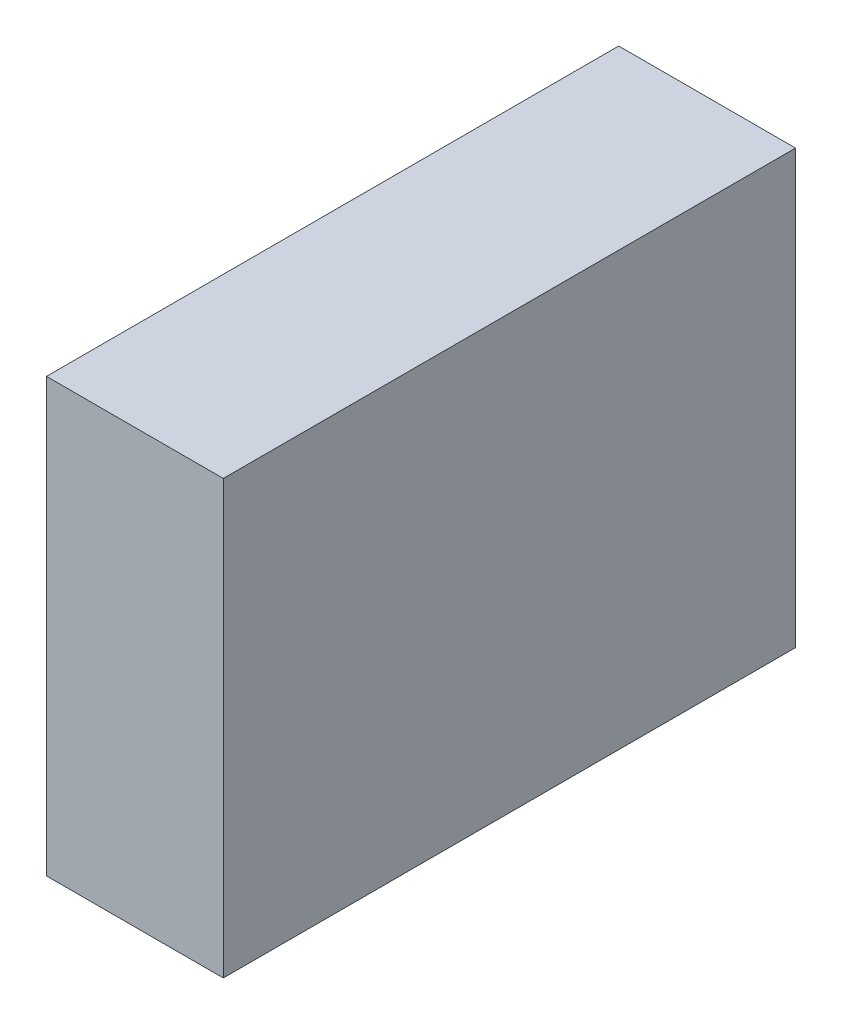
SolidWorks part; units mm, degrees
ref_plane "Front" through (0, 0, 0) normal (0, 0, 1) x (1, 0, 0)
ref_plane "Top" through (0, 0, 0) normal (0, 1, 0) x (1, 0, 0)
ref_plane "Right" through (0, 0, 0) normal (1, 0, 0) x (0, 0, -1)
sketch "Sketch1" plane through (0, 0, 0) normal (0, 1, 0) x (1, 0, 0)
  line L0 (0, 0) -> (613, 0)
  line L1 (0, 0) -> (0, 1984)
  line L2 (0, 1984) -> (613, 1984)
  line L3 (613, 0) -> (613, 1984)
  dimension "D1" = 613
  dimension "D2" = 1984
extrude "Boss-Extrude1" add sketch "Sketch1" along normal blind 1500
equation "\"Height\"= 1500"
equation "\"D1@Boss-Extrude1\"=\"Height\""
